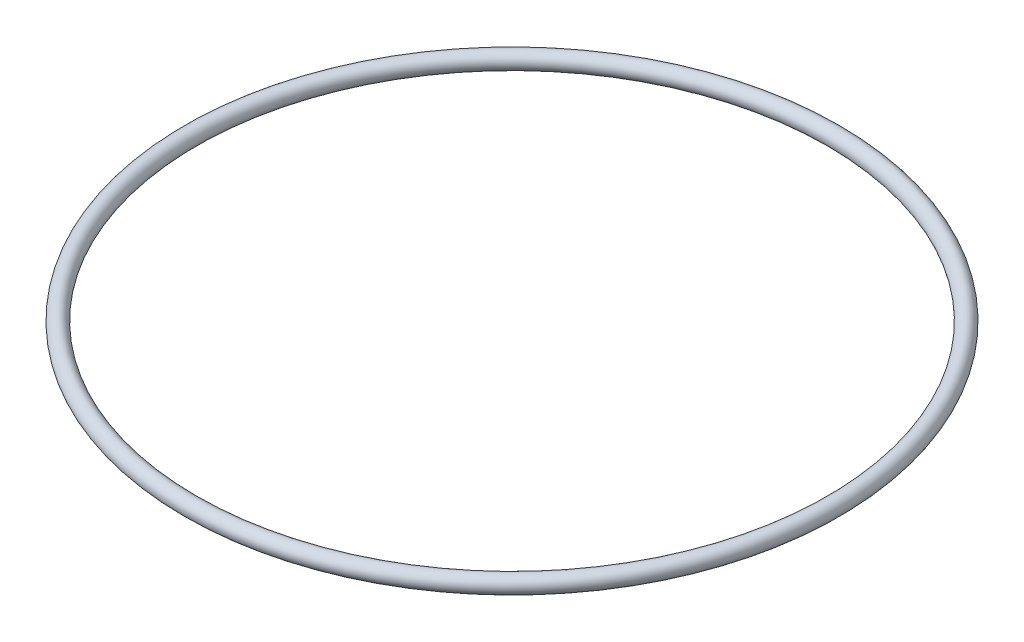
SolidWorks part; units mm, degrees
ref_plane "Front Plane" through (0, 0, 0) normal (0, 0, 1) x (1, 0, 0)
ref_plane "Top Plane" through (0, 0, 0) normal (0, 1, 0) x (1, 0, 0)
ref_plane "Right Plane" through (0, 0, 0) normal (1, 0, 0) x (0, 0, -1)
sketch "Sketch1" plane through (0, 0, 0) normal (0, 0, 1) x (1, 0, 0)
  line L0 (0, -4.8684) -> (0, 7.2595) construction
  circle A0 centre (34.145, 0) radius 0.89
  dimension "D1" = 1.78
  dimension "D2" = 68.29
revolve "Revolve1" add sketch "Sketch1" angle 360 about L0
